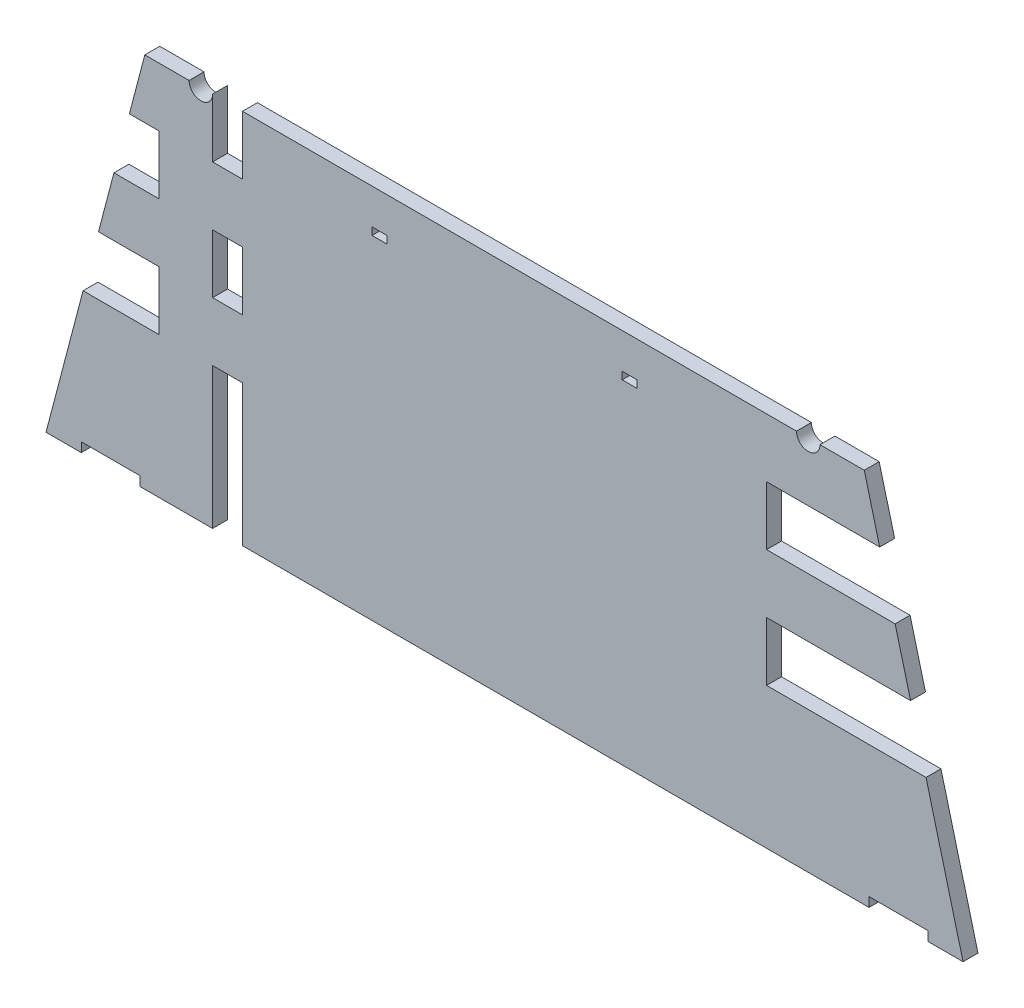
SolidWorks part; units mm, degrees
ref_plane "Front Plane" through (0, 0, 0) normal (0, 0, 1) x (1, 0, 0)
ref_plane "Top Plane" through (0, 0, 0) normal (0, 1, 0) x (1, 0, 0)
ref_plane "Right Plane" through (0, 0, 0) normal (1, 0, 0) x (0, 0, -1)
sketch "Sketch1" plane through (0, 0, 0) normal (0, 0, 1) x (1, 0, 0)
  line L0 (-155, 0) -> (-155, 4)
  line L1 (155, 0) -> (-111.4437, 0)
  line L2 (-155, 4) -> (-180, 4)
  line L3 (-180, 4) -> (-180, 0)
  line L4 (-180, 0) -> (-195, 0)
  line L5 (-195, 0) -> (-179.2417, 60)
  line L6 (-179.2417, 60) -> (-146.8438, 60)
  line L7 (-146.8438, 85) -> (-146.8438, 60)
  line L8 (111.4437, 60) -> (111.4437, 0) construction
  line L12 (-146.8438, 85) -> (-172.6757, 85)
  line L13 (-172.6757, 85) -> (-166.1097, 110)
  line L14 (-166.1097, 110) -> (-146.8438, 110)
  line L15 (-146.8438, 110) -> (-146.8438, 135)
  line L16 (-146.8438, 135) -> (-159.5438, 135)
  line L17 (-159.5438, 135) -> (-152.9778, 160)
  line L18 (-152.9778, 160) -> (-134.1438, 160)
  line L19 (-146.8438, 135) -> (-146.8438, 160) construction
  line L20 (-124.1438, 160) -> (-124.1437, 135)
  line L21 (-124.1437, 135) -> (-111.4437, 135)
  line L22 (-111.4437, 135) -> (-111.4437, 160)
  line L23 (-111.4437, 160) -> (0, 160)
  line L24 (-50, 145) -> (-50, 141.825)
  line L25 (-50, 141.825) -> (-56.35, 141.825)
  line L26 (-56.35, 141.825) -> (-56.35, 145)
  line L27 (-56.35, 145) -> (-50, 145)
  line L28 (-146.8438, 110) -> (-146.8438, 85) construction
  line L30 (-146.8438, 60) -> (-146.8438, 0) construction
  line L31 (0, 160) -> (0, 0) construction
  line L32 (-124.1437, 110) -> (-124.1437, 85)
  line L34 (111.4437, 110) -> (111.4437, 85) construction
  line L35 (111.4437, 135) -> (111.4437, 160) construction
  line L36 (56.35, 145) -> (50, 145)
  line L37 (56.35, 141.825) -> (56.35, 145)
  line L38 (50, 141.825) -> (56.35, 141.825)
  line L39 (50, 145) -> (50, 141.825)
  line L40 (0, 160) -> (124.1437, 160)
  line L41 (-124.1437, 85) -> (-111.4437, 85)
  line L42 (-111.4437, 85) -> (-111.4437, 110)
  line L43 (152.9778, 160) -> (134.1438, 160)
  line L44 (159.5438, 135) -> (152.9778, 160)
  line L45 (111.4437, 135) -> (159.5438, 135)
  line L46 (111.4437, 110) -> (111.4437, 135)
  line L47 (166.1097, 110) -> (111.4437, 110)
  line L48 (172.6757, 85) -> (166.1097, 110)
  line L49 (111.4437, 85) -> (172.6757, 85)
  line L50 (111.4437, 60) -> (111.4437, 85)
  line L55 (179.2417, 60) -> (111.4437, 60)
  line L56 (195, 0) -> (179.2417, 60)
  line L57 (180, 0) -> (195, 0)
  line L58 (180, 4) -> (180, 0)
  line L59 (155, 4) -> (180, 4)
  line L60 (155, 0) -> (155, 4)
  line L61 (-111.4437, 110) -> (-124.1437, 110)
  line L66 (-124.1438, 60) -> (-124.1437, 0)
  line L67 (-124.1438, 60) -> (-111.4438, 60)
  line L68 (-111.4438, 60) -> (-111.4437, 0)
  line L69 (-124.1437, 0) -> (-155, 0)
  arc A0 (-124.1438, 160) -> (-134.1438, 160) centre (-129.1438, 160) cw
  arc A1 (124.1437, 160) -> (134.1438, 160) centre (129.1438, 160) ccw
  dimension "D7" = 6.35
  dimension "D2" = 5
  dimension "D1" = 12.7
  dimension "D3" = 4
  dimension "D4" = 25
  dimension "D5" = 160
  dimension "D6" = 15
  dimension "D8" = 3.175
  dimension "D9" = 15
  dimension "D10" = 50
  dimension "D11" = 12.7
  dimension "D12" = 12.7
  dimension "D13" = 155
  dimension "D14" = 134.1438
  dimension "D15" = 12.7
  dimension "D16" = 60
extrude "Extrude1" add sketch "Sketch1" along normal blind 6.35
